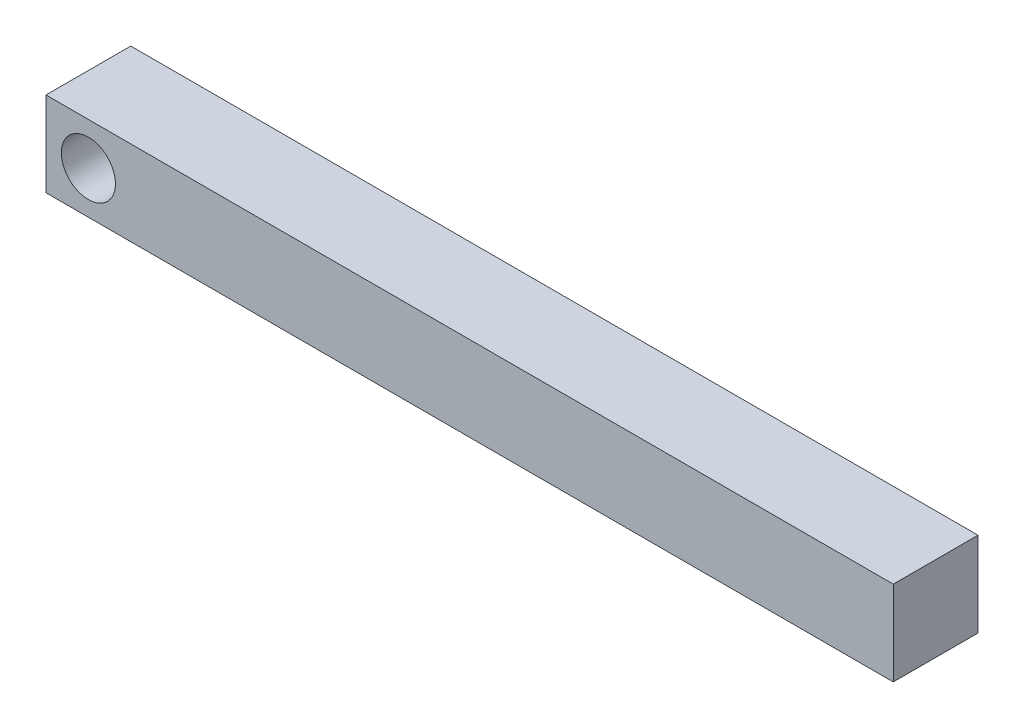
SolidWorks part; units mm, degrees
ref_plane "Front Plane" through (0, 0, 0) normal (0, 0, 1) x (1, 0, 0)
ref_plane "Top Plane" through (0, 0, 0) normal (0, 1, 0) x (1, 0, 0)
ref_plane "Right Plane" through (0, 0, 0) normal (1, 0, 0) x (0, 0, -1)
sketch "Sketch1" plane through (0, 0, 0) normal (0, 1, 0) x (1, 0, 0)
  line L1 (-69.1021, 39.3264) -> (130.8979, 39.3264)
  line L2 (-69.1021, 39.3264) -> (-69.1021, 19.3264)
  line L3 (-69.1021, 19.3264) -> (130.8979, 19.3264)
  line L4 (130.8979, 39.3264) -> (130.8979, 19.3264)
  dimension "D1" = 200
  dimension "D2" = 20
extrude "Extrude1" add sketch "Sketch1" along normal blind 20
sketch "Sketch2" plane through (0, 0, -19.3264) normal (0, 0, 1) x (1, 0, 0)
  line L1 (-69.1021, 20) -> (130.8979, 20) construction
  line L2 (-69.1021, 20) -> (-69.1021, 0) construction
  circle A0 centre (-59.1021, 10) radius 6.3867
  dimension "D1" = 10
  dimension "D2" = 10
extrude "Cut-Extrude1" cut sketch "Sketch2" against normal through all
